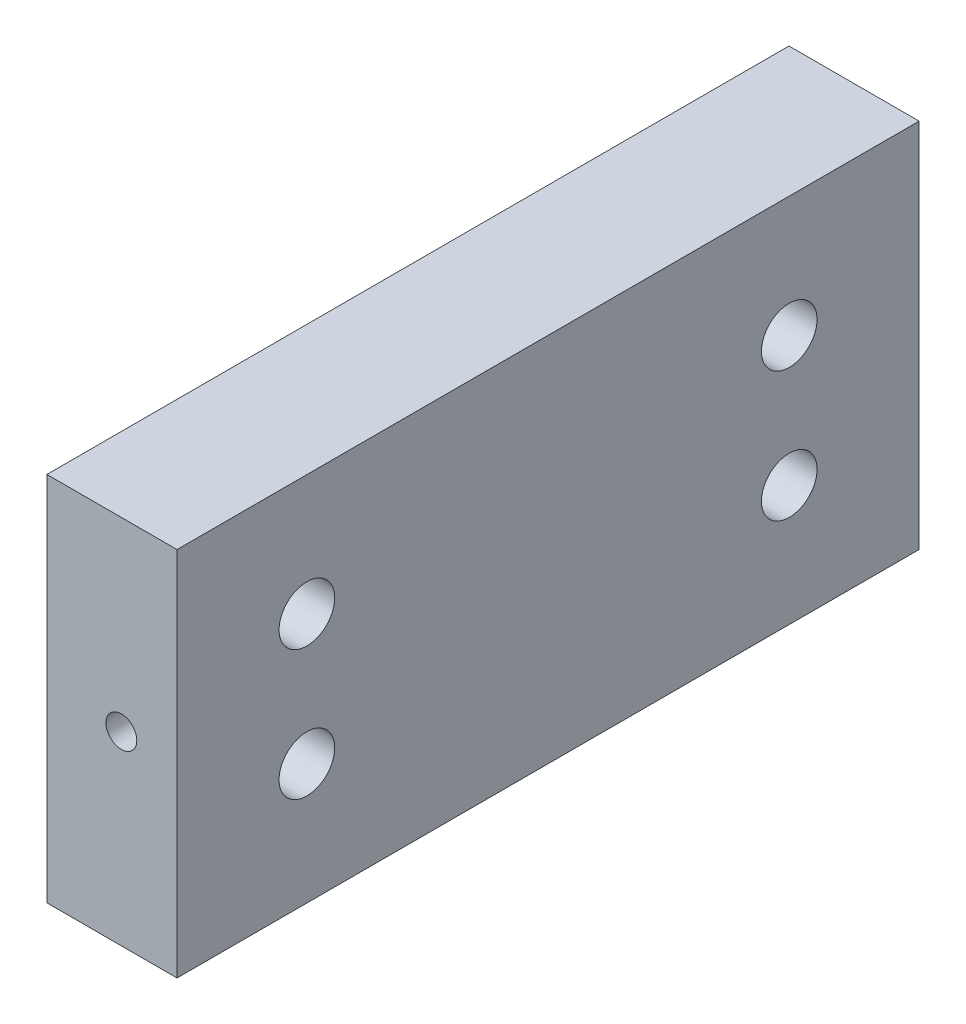
SolidWorks part; units mm, degrees
ref_plane "Ebene vorne" through (0, 0, 0) normal (0, 0, 1) x (1, 0, 0)
ref_plane "Ebene oben" through (0, 0, 0) normal (0, 1, 0) x (1, 0, 0)
ref_plane "Ebene rechts" through (0, 0, 0) normal (1, 0, 0) x (0, 0, -1)
sketch "Skizze1" plane through (0, 0, 0) normal (0, 0, 1) x (1, 0, 0)
  line L1 (17.5347, -50) -> (-17.5347, -50)
  line L2 (17.5347, -50) -> (17.5347, 50)
  line L3 (17.5347, 50) -> (-17.5347, 50)
  line L4 (-17.5347, -50) -> (-17.5347, 50)
  line L5 (17.5347, -50) -> (-17.5347, 50) construction
  line L6 (17.5347, 50) -> (-17.5347, -50) construction
  point P0 (0, 0)
  dimension "D1" = 100
  dimension "D2" = 35.0694
extrude "Aufsatz-Linear austragen1" add sketch "Skizze1" along normal blind 200
ref_plane "Ebene1" through (0, 0, 100) normal (0, 0, 1) x (1, 0, 0)
sketch "Skizze7" plane through (17.5347, 0, 0) normal (1, 0, 0) x (0, 0, -1)
  line L1 (-200, 50) -> (0, 50) construction
  line L2 (-200, -50) -> (-200, 50) construction
  circle A0 centre (-165, 17.5) radius 32.5
  dimension "D1" = 65
  dimension "D2" = 35
hole_wizard "Stirnsenkung für M8 Senkschraube (Kopf Button)1" positions "Skizze9" profile "Skizze8" counterbore size "M8" standard "ANSI Metrisch" end condition through all
sketch "Skizze9" plane through (17.5347, 0, 0) normal (1, 0, 0) x (0, 0, -1)
  point P0 (-165, 17.5)
sketch "Skizze8" plane through (17.5347, 17.5, 165) normal (0, 1, 0) x (0, 0, -1)
  line L0 (0, 0) -> (0, 35.0694)
  line L1 (0, 35.0694) -> (4.5, 35.0694)
  line L3 (4.5, 35.0694) -> (4.5, 25)
  line L4 (4.5, 25) -> (7.5, 25)
  line L5 (7.5, 25) -> (7.5, 0)
  line L7 (7.5, 0) -> (0, 0)
  line L11 (0, -6.35) -> (0, 107.95) construction
  dimension "Bohrerdurchmesser" = 9
  dimension "Bohrungstiefe" = 35.0694
  dimension "Senkdurchmesser2" = 15
  dimension "Senktiefe2" = 25
mirror "Spiegeln1" [suppressed] about plane through (0, 0, 100) normal (0, 0, 1)
mirror "Spiegeln2" [suppressed] about plane through (0, 0, 0) normal (0, 1, 0)
mirror "Spiegeln3" about plane through (0, 0, 100) normal (0, 0, 1) of "Stirnsenkung für M8 Senkschraube (Kopf Button)1"
mirror "Spiegeln4" about plane through (0, 0, 0) normal (0, 1, 0) of "Spiegeln3", "Stirnsenkung für M8 Senkschraube (Kopf Button)1"
hole_wizard "Kernloch für M8 Helicoil1" positions "Skizze11" profile "Skizze10" hole size "M8x1.25" standard "ANSI Metrisch"
sketch "Skizze11" plane through (0, 0, 200) normal (0, 0, 1) x (1, 0, 0)
  point P0 (2.5347, 0)
sketch "Skizze10" plane through (2.5347, 0, 200) normal (1, 0, 0) x (0, -1, 0)
  line L0 (0, 0) -> (0, 22.4936)
  line L1 (0, 22.4936) -> (4.15, 20)
  line L2 (4.15, 20) -> (4.15, 0)
  line L5 (4.15, 0) -> (0, 0)
  line L10 (0, 22.4936) -> (-4.15, 20) construction
  line L11 (0, -6.35) -> (0, 107.95) construction
  dimension "Bohrerdurchmesser" = 8.3
  dimension "Bohrungstiefe" = 20
  dimension "Spitzenwinkel" = 118
